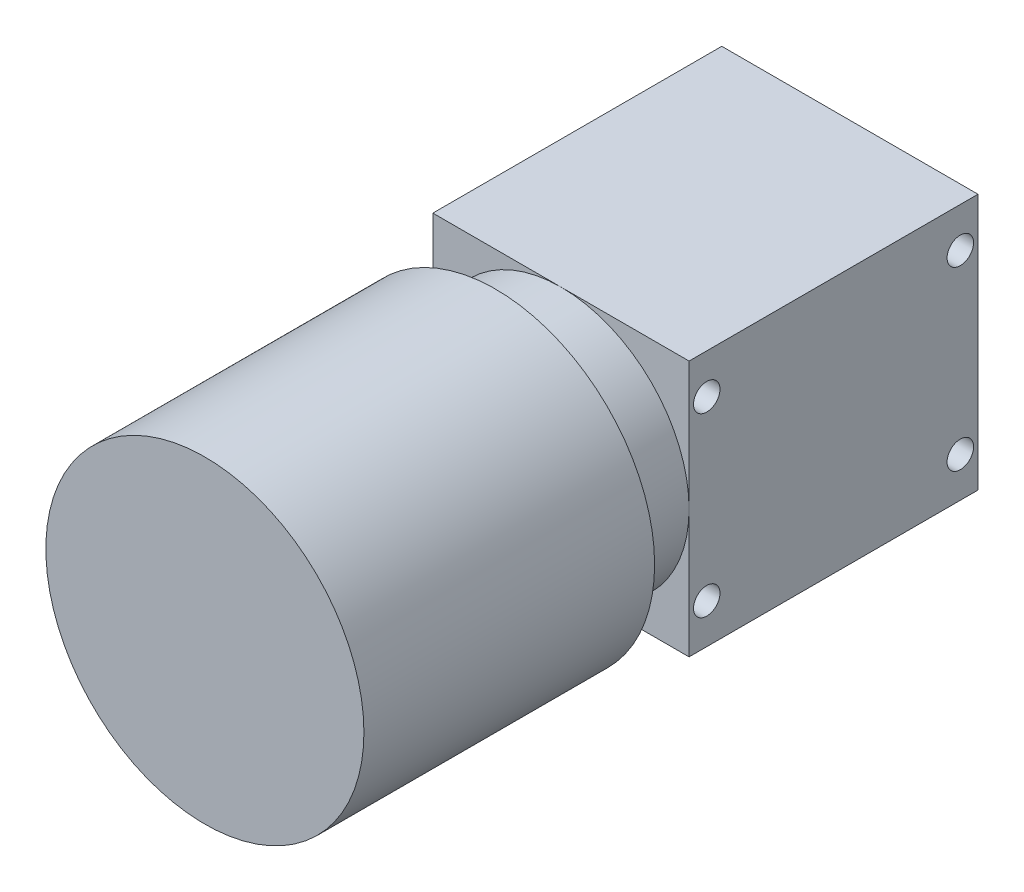
SolidWorks part; units mm, degrees
ref_plane "前视基准面" through (0, 0, 0) normal (0, 0, 1) x (1, 0, 0)
ref_plane "上视基准面" through (0, 0, 0) normal (0, 1, 0) x (1, 0, 0)
ref_plane "右视基准面" through (0, 0, 0) normal (1, 0, 0) x (0, 0, -1)
sketch "草图1" plane through (0, 0, 0) normal (0, 0, 1) x (1, 0, 0)
  line L5 (-14.5, -14.5) -> (14.5, -14.5)
  line L6 (-14.5, -14.5) -> (-14.5, 14.5)
  line L7 (-14.5, 14.5) -> (14.5, 14.5)
  line L8 (14.5, -14.5) -> (14.5, 14.5)
  line L9 (0, 14.5) -> (0, -14.5) construction
  line L10 (-14.5, 0) -> (14.5, 0) construction
  point P0 (0, 0)
  dimension "D1" = 29
  dimension "D2" = 29
extrude "凸台-拉伸1" add sketch "草图1" along normal blind 32.7
sketch "草图2" plane through (0, 0, 32.7) normal (0, 0, 1) x (1, 0, 0)
  circle A0 centre (0, 0) radius 14.5
  circle A1 centre (0, 0) radius 12.9959
extrude "凸台-拉伸2" add sketch "草图2" along normal blind 7.4
sketch "草图3" plane through (-14.5, 0, 0) normal (-1, 0, 0) x (0, 0, 1)
  line L0 (32.7, -14.5) -> (0, -14.5) construction
  line L1 (2, -10) -> (30.7, -10) construction
  line L2 (2, -10) -> (2, 10) construction
  line L3 (2, 10) -> (30.7, 10) construction
  line L4 (30.7, -10) -> (30.7, 10) construction
  line L5 (16.35, 10) -> (16.35, -10) construction
  line L6 (2, 0) -> (30.7, 0) construction
  circle A0 centre (2, 10) radius 1.5
  circle A1 centre (30.7, 10) radius 1.5
  circle A2 centre (30.7, -10) radius 1.5
  circle A3 centre (2, -10) radius 1.5
  point P0 (16.35, 0)
  point P7 (16.35, -14.5)
  dimension "D3" = 3
  dimension "D1" = 28.7
  dimension "D2" = 20
extrude "切除-拉伸1" cut sketch "草图3" against normal blind 42.4
sketch "草图4" plane through (0, 0, 40.1) normal (0, 0, 1) x (1, 0, 0)
  circle A0 centre (0, 0) radius 18
  dimension "D1" = 36
extrude "凸台-拉伸3" add sketch "草图4" along normal blind 32.9
sketch "草图5" plane through (0, 0, 0) normal (0, 1, 0) x (1, 0, 0)
  line L0 (0, 0) -> (0, -80.1358) construction
  line L1 (0, -40.1) -> (-37.3992, -190.1)
  line L2 (18, -40.1) -> (-18, -40.1) construction
  line L4 (0, -40.1) -> (37.3992, -190.1)
  dimension "D1" = 14
  dimension "D2" = 14
surface "曲面-拉伸1" sketch "草图5" parameters "D1"=80, "D2"=80
sketch "草图6" plane through (0, 0, 0) normal (1, 0, 0) x (0, 0, -1)
  line L0 (-40.1, 0) -> (-190.1, 37.3992)
  line L2 (-40.1, 0) -> (-190.1, -37.3992)
  line L3 (-40.1, 0) -> (-147.6413, 0) construction
  line L5 (-40.1, -80) -> (-40.1, 80) construction
  line L6 (-40.1, -14.5) -> (-40.1, 14.5) construction
  dimension "D1" = 14
  dimension "D2" = 14
  dimension "D4" = 150
surface "曲面-拉伸2" sketch "草图6" parameters "D1"=80, "D2"=80
surface "曲面-剪裁1"
surface "曲面-剪裁2"
surface "曲面-剪裁3"
surface "曲面-剪裁4"
